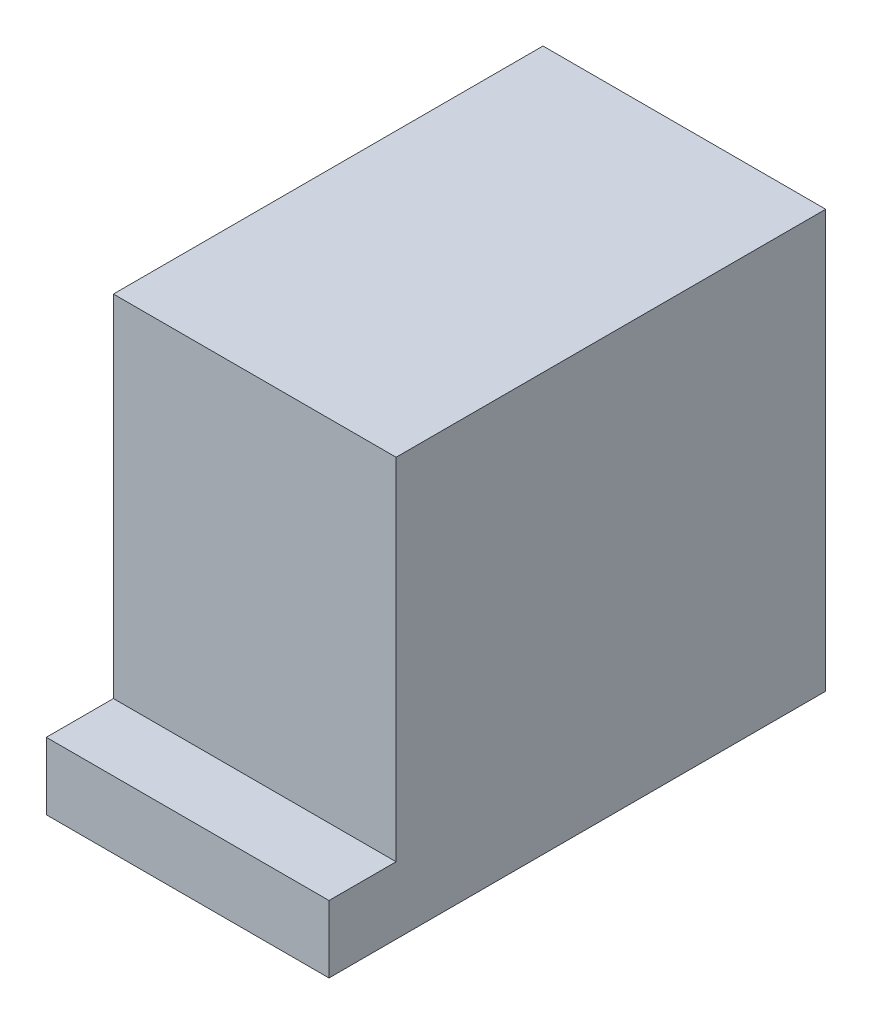
SolidWorks part; units mm, degrees
ref_plane "Front Plane" through (0, 0, 0) normal (0, 0, 1) x (1, 0, 0)
ref_plane "Top Plane" through (0, 0, 0) normal (0, 1, 0) x (1, 0, 0)
ref_plane "Right Plane" through (0, 0, 0) normal (1, 0, 0) x (0, 0, -1)
sketch "Sketch1" plane through (0, 0, 0) normal (0, 1, 0) x (1, 0, 0)
  line L1 (107, -188) -> (-107, -188)
  line L2 (107, -188) -> (107, 188)
  line L3 (107, 188) -> (-107, 188)
  line L4 (-107, -188) -> (-107, 188)
  line L5 (107, -188) -> (-107, 188) construction
  line L6 (107, 188) -> (-107, -188) construction
  point P0 (0, 0)
  dimension "D1" = 376
  dimension "D2" = 214
extrude "Boss-Extrude1" add sketch "Sketch1" along normal blind 50.8
sketch "Sketch2" plane through (0, 50.8, 0) normal (0, 1, 0) x (1, 0, 0)
  line L0 (107, -188) -> (107, 188) construction
  line L1 (-107, 188) -> (107, 188)
  line L2 (-107, 188) -> (-107, -137.2)
  line L3 (-107, -137.2) -> (107, -137.2)
  line L4 (107, 188) -> (107, -137.2)
  line L5 (-107, -188) -> (107, -188) construction
  dimension "D1" = 50.8
extrude "Boss-Extrude2" add sketch "Sketch2" along normal blind 316 from surface at -50.8 starting at face at (0, 0, 0)
